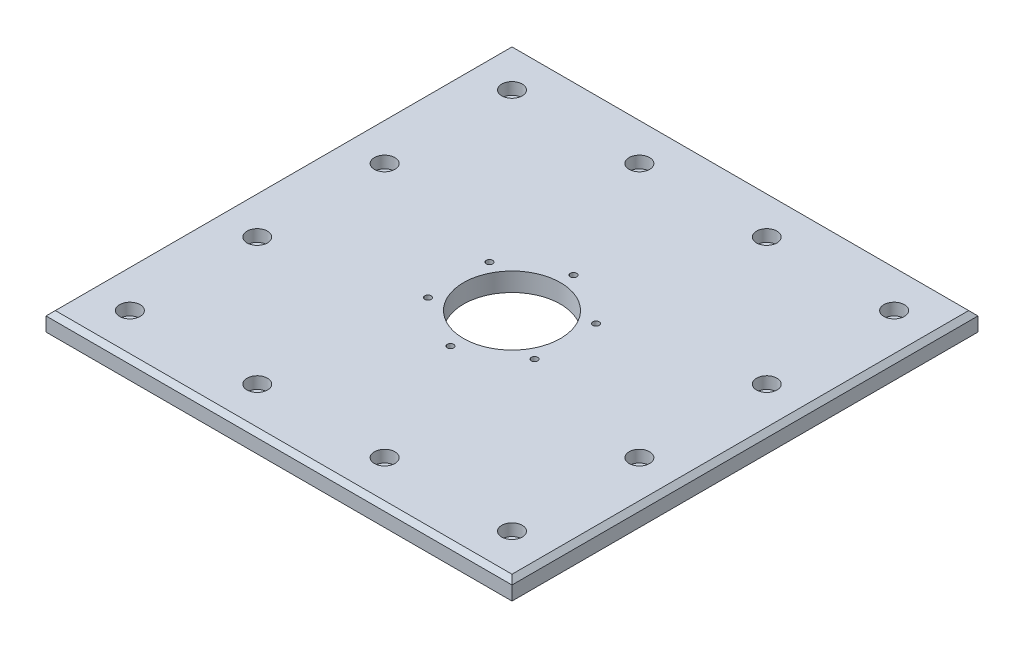
SolidWorks part; units mm, degrees
ref_plane "Ebene vorne" through (0, 0, 0) normal (0, 0, 1) x (1, 0, 0)
ref_plane "Ebene oben" through (0, 0, 0) normal (0, 1, 0) x (1, 0, 0)
ref_plane "Ebene rechts" through (0, 0, 0) normal (1, 0, 0) x (0, 0, -1)
sketch "Sketch1" plane through (0, 0, 0) normal (0, 1, 0) x (1, 0, 0)
  line L0 (0, -29) -> (0, -37) construction
  line L1 (-125, -125) -> (125, -125)
  line L2 (-125, -125) -> (-125, 125)
  line L3 (-125, 125) -> (125, 125)
  line L4 (125, -125) -> (125, 125)
  line L5 (-125, -125) -> (125, 125) construction
  line L6 (-125, 125) -> (125, -125) construction
  line L8 (-102.5, -102.5) -> (102.5, -102.5) construction
  line L9 (-102.5, -102.5) -> (-102.5, 102.5) construction
  line L10 (-102.5, 102.5) -> (102.5, 102.5) construction
  line L11 (102.5, -102.5) -> (102.5, 102.5) construction
  line L12 (-102.5, -102.5) -> (102.5, 102.5) construction
  line L13 (-102.5, 102.5) -> (102.5, -102.5) construction
  circle A0 centre (0, 0) radius 26
  circle A1 centre (0, 0) radius 29 construction
  circle A2 centre (0, 0) radius 37
  point P0 (0, 0)
  point P12 (0, -33)
  point P13 (-28.5788, -16.5)
  point P16 (-28.5788, 16.5)
  point P17 (0, 33)
  point P18 (28.5788, 16.5)
  point P19 (28.5788, -16.5)
  point P20 (0, 0)
  point P24 (-102.5, 102.5)
  point P27 (-34.1667, 102.5)
  point P28 (34.1667, 102.5)
  point P29 (102.5, 102.5)
  point P30 (-34.1667, 34.1667)
  point P31 (34.1667, 34.1667)
  point P32 (102.5, 34.1667)
  point P33 (-34.1667, -34.1667)
  point P34 (34.1667, -34.1667)
  point P35 (102.5, -34.1667)
  point P36 (-34.1667, -102.5)
  point P37 (34.1667, -102.5)
  point P38 (102.5, -102.5)
  point P39 (-102.5, 34.1667)
  point P40 (-102.5, -34.1667)
  point P41 (-102.5, -102.5)
  dimension "D2" = 52
  dimension "D3" = 58
  dimension "D4" = 8
  dimension "D1" = 250
  dimension "D5" = 6
  dimension "D6" = 205
  dimension "D7" = 4
  dimension "D8" = 4
extrude "Boss-Extrude1" add sketch "Sketch1" along normal blind 10 contours L1 L4 L3 L2 A2 | A2 A0
hole_wizard "M3 Clearance Hole1" positions "Sketch2" profile "Sketch3" hole size "M3" standard "DIN" end condition through all
sketch "Sketch2" plane through (0, 10, 0) normal (0, 1, 0) x (1, 0, 0)
  point P0 (0, 33)
  point P3 (28.5788, 16.5)
  point P6 (28.5788, -16.5)
  point P9 (0, -33)
  point P12 (-28.5788, -16.5)
  point P15 (-28.5788, 16.5)
sketch "Sketch3" plane through (0, 10, -33) normal (1, 0, 0) x (0, 0, 1)
  line L0 (0, 0) -> (0, 10)
  line L1 (0, 10) -> (1.7, 10)
  line L2 (1.7, 10) -> (1.7, 0)
  line L5 (1.7, 0) -> (0, 0)
  line L11 (0, -6.35) -> (0, 107.95) construction
  dimension "Thru Hole Dia." = 3.4
  dimension "Thru Hole Depth" = 10
hole_wizard "CBORE for M6 Hex Socket Head Cap Screw1" positions "Sketch4" profile "Sketch5" counterbore size "M6" standard "DIN" end condition through all
sketch "Sketch4" plane through (0, 10, 0) normal (0, 1, 0) x (1, 0, 0)
  point P0 (-102.5, 102.5)
  point P3 (-34.1667, 102.5)
  point P6 (34.1667, 102.5)
  point P9 (102.5, 102.5)
  point P12 (102.5, 34.1667)
  point P15 (102.5, -34.1667)
  point P18 (102.5, -102.5)
  point P21 (34.1667, -102.5)
  point P24 (-34.1667, -102.5)
  point P27 (-102.5, -102.5)
  point P30 (-102.5, -34.1667)
  point P33 (-102.5, 34.1667)
sketch "Sketch5" plane through (-102.5, 10, -102.5) normal (1, 0, 0) x (0, 0, 1)
  line L0 (0, 0) -> (0, 10)
  line L1 (0, 10) -> (3.3, 10)
  line L3 (3.3, 10) -> (3.3, 6.4)
  line L4 (3.3, 6.4) -> (5.5, 6.4)
  line L5 (5.5, 6.4) -> (5.5, 0)
  line L7 (5.5, 0) -> (0, 0)
  line L11 (0, -6.35) -> (0, 107.95) construction
  dimension "Thru Hole Dia." = 6.6
  dimension "Thru Hole Depth" = 10
  dimension "C'Bore Dia." = 11
  dimension "C'Bore Depth" = 6.4
chamfer "2,5mm Chamfer1" distance 2.5 angle 45 4 edges at (-125, 10, 0) (0, 10, -125) (125, 10, 0) (0, 10, 125)
